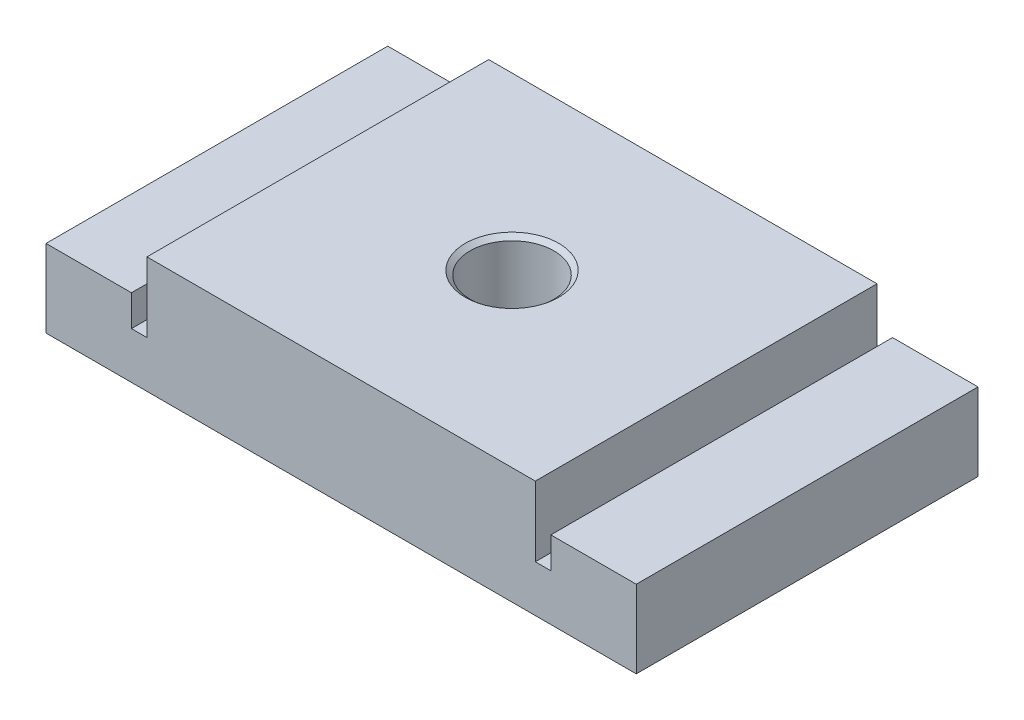
SolidWorks part; units mm, degrees
ref_plane "Front Plane" through (0, 0, 0) normal (0, 0, 1) x (1, 0, 0)
ref_plane "Top Plane" through (0, 0, 0) normal (0, 1, 0) x (1, 0, 0)
ref_plane "Right Plane" through (0, 0, 0) normal (1, 0, 0) x (0, 0, -1)
sketch "Sketch1" plane through (0, 0, 0) normal (0, 0, 1) x (1, 0, 0)
  line L0 (0, 0) -> (0, 32.4858) construction
  line L1 (-38, 0) -> (-38, 10)
  line L2 (-38, 10) -> (-27, 10)
  line L3 (-27, 10) -> (-27, 6)
  line L4 (-27, 6) -> (-25, 6)
  line L5 (-25, 6) -> (-25, 15)
  line L6 (25, 6) -> (25, 15)
  line L7 (27, 6) -> (25, 6)
  line L8 (27, 10) -> (27, 6)
  line L9 (38, 10) -> (27, 10)
  line L10 (38, 0) -> (38, 10)
  line L11 (-25, 15) -> (25, 15)
  line L12 (-38, 0) -> (38, 0)
  dimension "D1" = 76
  dimension "D2" = 15
  dimension "D3" = 10
  dimension "D4" = 2
  dimension "D5" = 9
  dimension "D6" = 50
extrude "Boss-Extrude1" add sketch "Sketch1" along normal mid plane 44
hole_wizard "M12x1.25 Tapped Hole1" positions "Sketch2" profile "Sketch3" tap size "M12x1.25" standard "ANSI Metric" end condition up to next
sketch "Sketch2" plane through (0, 15, 0) normal (0, 1, 0) x (1, 0, 0)
  point P0 (0, 0)
sketch "Sketch3" plane through (0, 15, 0) normal (1, 0, 0) x (0, 0, 1)
  line L0 (0, 0) -> (0, 15)
  line L1 (0, 15) -> (5.4, 15)
  line L2 (5.4, 15) -> (5.4, 0.5244)
  line L3 (5.4, 0.5244) -> (6.025, 0)
  line L5 (6.025, 0) -> (0, 0)
  line L6 (-5.4, 0.5244) -> (-6.025, 0) construction
  line L11 (0, -6.35) -> (0, 107.95) construction
  dimension "Thru Tap Drill Dia." = 10.8
  dimension "Thru Tap Drill Depth" = 15
  dimension "Near C'Sink Dia." = 12.05
  dimension "Near C'Sink Angle" = 100
cosmetic thread "Hole Thread1" parameters "D2"=12
